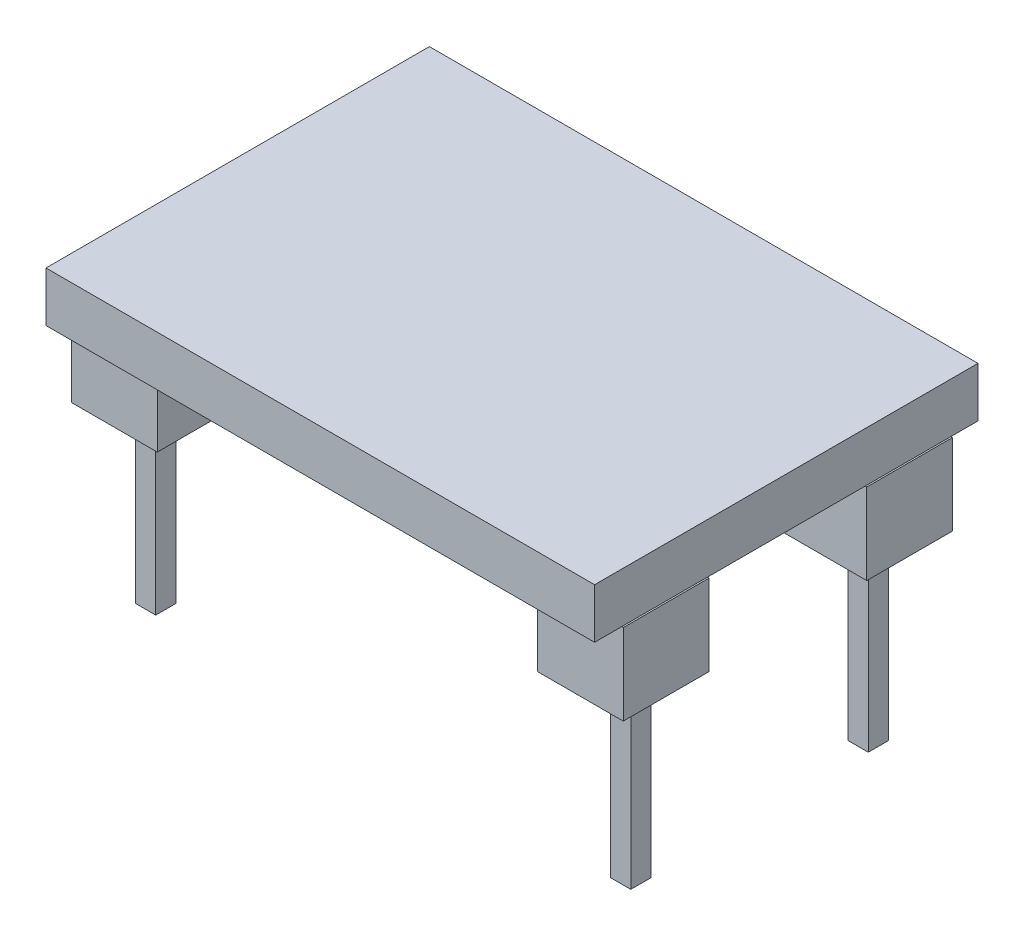
SolidWorks part; units mm, degrees
ref_plane "Front Plane" through (0, 0, 0) normal (0, 0, 1) x (1, 0, 0)
ref_plane "Top Plane" through (0, 0, 0) normal (0, 1, 0) x (1, 0, 0)
ref_plane "Right Plane" through (0, 0, 0) normal (1, 0, 0) x (0, 0, -1)
sketch "Sketch1" plane through (0, 0, 0) normal (0, 1, 0) x (1, 0, 0)
  line L0 (-8.8, -6.15) -> (8.8, 6.15) construction
  line L1 (-8.8, 6.15) -> (8.8, 6.15)
  line L2 (-8.8, 6.15) -> (-8.8, -6.15)
  line L3 (-8.8, -6.15) -> (8.8, -6.15)
  line L4 (8.8, 6.15) -> (8.8, -6.15)
  dimension "D1" = 17.6
  dimension "D2" = 12.3
extrude "Boss-Extrude1" add sketch "Sketch1" along normal blind 1.6
sketch "Sketch2" plane through (0, 0, 0) normal (0, -1, 0) x (1, 0, 0)
  line L0 (0, 0) -> (0, 3.7826) construction
  line L1 (-8.85, 5.28) -> (-6.1, 5.28)
  line L2 (-8.85, 5.28) -> (-8.85, 2.53)
  line L3 (-8.85, 2.53) -> (-6.1, 2.53)
  line L4 (-6.1, 5.28) -> (-6.1, 2.53)
  line L5 (0, 0) -> (-4.4697, 0) construction
  line L6 (-6.1, -5.28) -> (-6.1, -2.53)
  line L7 (-8.85, -2.53) -> (-6.1, -2.53)
  line L8 (-8.85, -5.28) -> (-8.85, -2.53)
  line L9 (-8.85, -5.28) -> (-6.1, -5.28)
  line L10 (8.85, -5.28) -> (6.1, -5.28)
  line L11 (8.85, -5.28) -> (8.85, -2.53)
  line L12 (8.85, -2.53) -> (6.1, -2.53)
  line L13 (6.1, -5.28) -> (6.1, -2.53)
  line L14 (6.1, 5.28) -> (6.1, 2.53)
  line L15 (8.85, 2.53) -> (6.1, 2.53)
  line L16 (8.85, 5.28) -> (8.85, 2.53)
  line L17 (8.85, 5.28) -> (6.1, 5.28)
  dimension "D1" = 2.75
  dimension "D2" = 5.06
  dimension "D3" = 12.2
extrude "Boss-Extrude2" add sketch "Sketch2" along normal blind 2.6
sketch "Sketch3" plane through (0, -2.6, 0) normal (0, -1, 0) x (1, 0, 0)
  line L0 (0, 0) -> (0, 3.1675) construction
  line L5 (0, 0) -> (2.9734, 0) construction
  line L19 (7.295, -3.485) -> (7.945, -3.485)
  line L20 (7.295, -3.485) -> (7.295, -4.135)
  line L21 (7.295, -4.135) -> (7.945, -4.135)
  line L22 (7.945, -3.485) -> (7.945, -4.135)
  line L23 (7.295, 4.135) -> (7.945, 4.135)
  line L24 (7.295, 4.135) -> (7.295, 3.485)
  line L25 (7.295, 3.485) -> (7.945, 3.485)
  line L26 (7.945, 4.135) -> (7.945, 3.485)
  line L27 (-7.945, -3.485) -> (-7.295, -3.485)
  line L28 (-7.945, -3.485) -> (-7.945, -4.135)
  line L29 (-7.945, -4.135) -> (-7.295, -4.135)
  line L30 (-7.295, -3.485) -> (-7.295, -4.135)
  line L31 (-7.945, 4.135) -> (-7.295, 4.135)
  line L32 (-7.945, 4.135) -> (-7.945, 3.485)
  line L33 (-7.945, 3.485) -> (-7.295, 3.485)
  line L34 (-7.295, 4.135) -> (-7.295, 3.485)
  point P20 (-7.2209, 6.9617)
  point P21 (-7.1829, -3.6309)
  point P22 (-7.945, -3.81)
  point P23 (-7.945, 3.81)
  point P24 (-7.62, 4.135)
  point P25 (7.62, 4.135)
  point P26 (10.5913, -3.1382)
  point P27 (-7.295, 3.81)
  dimension "D1" = 0.65
  dimension "D2" = 7.62
  dimension "D3" = 15.24
  dimension "D4" = 14.59
  dimension "D5" = 6.97
  dimension "D6" = 7.62
  dimension "D7" = 3.81
extrude "Boss-Extrude3" add sketch "Sketch3" along normal blind 5.7
